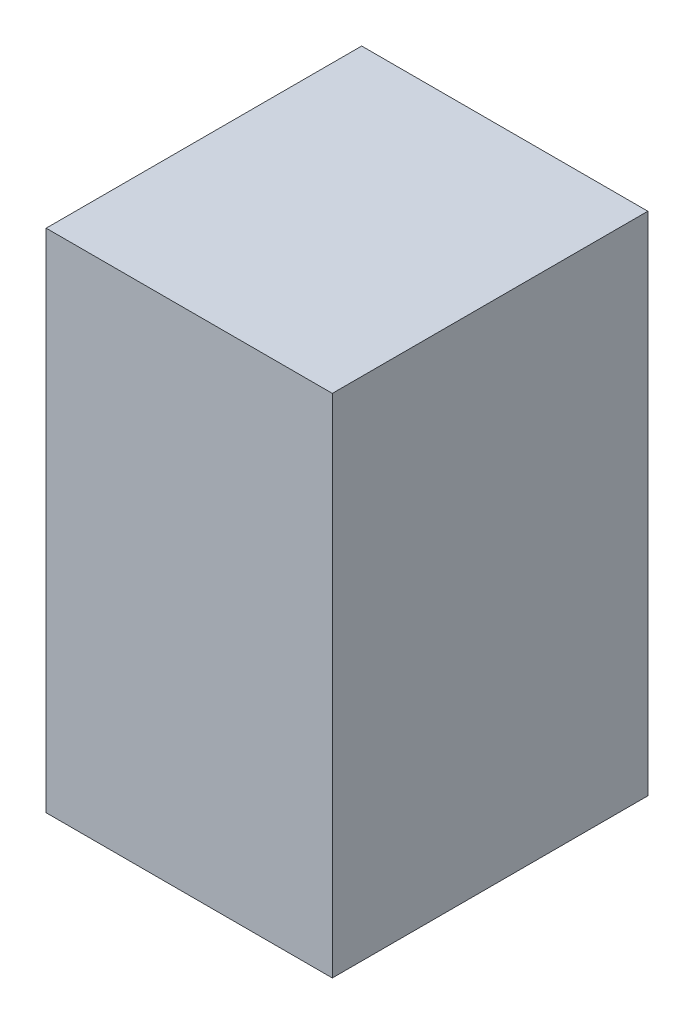
SolidWorks part; units mm, degrees
ref_plane "正面" through (0, 0, 0) normal (0, 0, 1) x (1, 0, 0)
ref_plane "平面" through (0, 0, 0) normal (0, 1, 0) x (1, 0, 0)
ref_plane "右側面" through (0, 0, 0) normal (1, 0, 0) x (0, 0, -1)
sketch "ｽｹｯﾁ1" plane through (0, 0, 0) normal (0, 0, 1) x (1, 0, 0)
  line L1 (-22.6516, 29.75) -> (16.3484, 29.75)
  line L2 (-22.6516, 29.75) -> (-22.6516, -39.25)
  line L3 (-22.6516, -39.25) -> (16.3484, -39.25)
  line L4 (16.3484, 29.75) -> (16.3484, -39.25)
  dimension "D1" = 69
  dimension "D2" = 39
  dimension "D3" = 39
  dimension "D4" = 69
extrude "ﾎﾞｽ - 押し出し1" add sketch "ｽｹｯﾁ1" along normal blind 43
